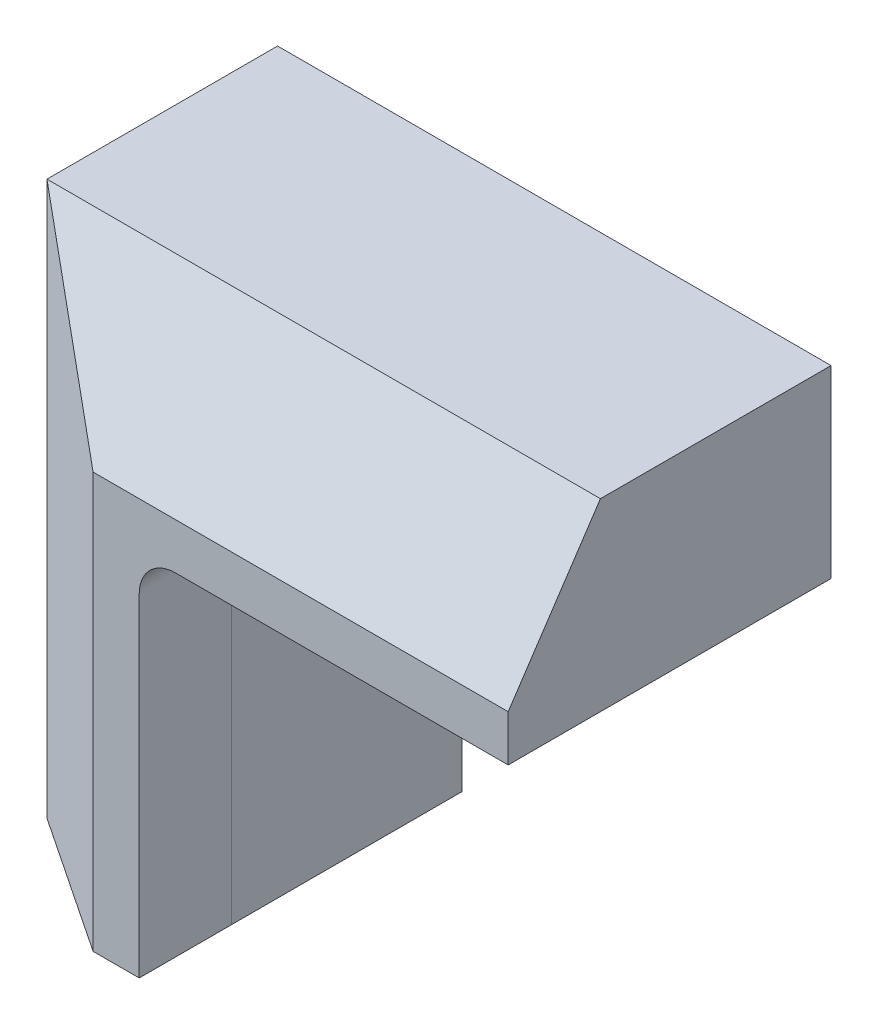
SolidWorks part; units mm, degrees
ref_plane "Front Plane" through (0, 0, 0) normal (0, 0, 1) x (1, 0, 0)
ref_plane "Top Plane" through (0, 0, 0) normal (0, 1, 0) x (1, 0, 0)
ref_plane "Right Plane" through (0, 0, 0) normal (1, 0, 0) x (0, 0, -1)
sketch "Sketch1" plane through (0, 0, 0) normal (0, 0, 1) x (1, 0, 0)
  line L2 (0, -1.999) -> (0, -20.32)
  line L3 (0, -20.32) -> (-10.16, -20.32)
  line L4 (-10.16, 0) -> (-10.16, -20.32)
  line L5 (1.999, 0) -> (20.32, 0)
  line L6 (-10.16, 0) -> (-10.16, 6.1595)
  line L7 (-6.1595, 10.16) -> (20.32, 10.16)
  line L8 (20.32, 0) -> (20.32, 10.16)
  line L9 (-6.1595, 10.16) -> (-10.16, 10.16)
  line L10 (-10.16, 10.16) -> (-10.16, 6.1595)
  arc A0 (1.999, 0) -> (0, -1.999) centre (1.999, -1.999) ccw
  point P6 (-10.16, 10.16)
  point P10 (0, 0)
  dimension "D5" = 1.999
  dimension "D1" = 10.16
  dimension "D2" = 10.16
  dimension "D3" = 20.32
  dimension "D4" = 20.32
extrude "Boss-Extrude1" add sketch "Sketch1" along normal blind 12.7
sketch "Sketch5" plane through (0, 0, 12.7) normal (0, 0, 1) x (1, 0, 0)
  line L0 (1.999, 0) -> (20.32, 0)
  line L1 (20.32, 0) -> (20.32, 10.16)
  line L2 (20.32, 10.16) -> (-10.16, 10.16)
  line L3 (-10.16, 10.16) -> (-10.16, -20.32)
  line L4 (-10.16, -20.32) -> (0, -20.32)
  line L5 (0, -20.32) -> (0, -1.999)
  arc A0 (0, -1.999) -> (1.999, 0) centre (1.999, -1.999) cw
ref_plane "Plane1" through (0, 0, 17.78) normal (0, 0, 1) x (1, 0, 0)
sketch "Sketch6" plane through (0, 0, 17.78) normal (0, 0, 1) x (1, 0, 0)
  line L0 (0, -1.999) -> (0, -20.32)
  line L1 (0, -20.32) -> (-2.54, -20.32)
  line L2 (-10.16, -20.32) -> (0, -20.32) construction
  line L3 (-2.54, -20.32) -> (-2.54, 2.54)
  line L4 (-2.54, 2.54) -> (20.32, 2.54)
  line L5 (20.32, 0) -> (20.32, 10.16) construction
  line L6 (20.32, 2.54) -> (20.32, 0)
  line L7 (20.32, 0) -> (1.999, 0)
  arc A0 (1.999, 0) -> (0, -1.999) centre (1.999, -1.999) ccw
  dimension "D1" = 2.54
  dimension "D2" = 2.54
sketch "Sketch4" plane through (0, 0, 0) normal (0, 0, 1) x (1, 0, 0)
  line L0 (0, 2.54) -> (20.32, 2.54) construction
  line L1 (20.32, 0) -> (20.32, 10.16) construction
  line L2 (1.999, 0) -> (20.32, 0) construction
  text T0 "<b>SHARP</b>"
  dimension "D1" = 2.54
extrude "Cut-Extrude1" cut sketch "Sketch4" along normal blind 2.54
loft "Loft1" add profiles "Sketch5", "Sketch6"
